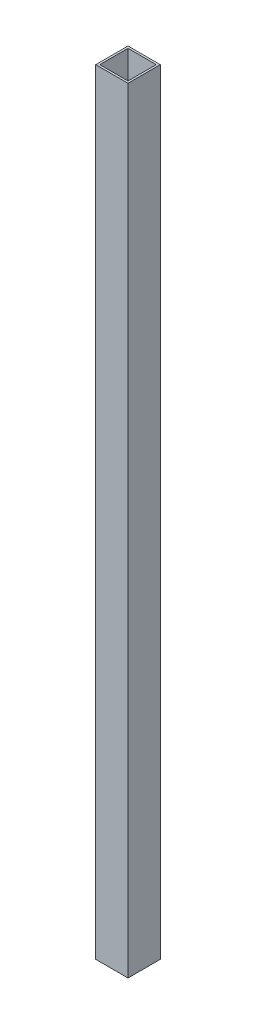
SolidWorks part; units mm, degrees
ref_plane "Front Plane" through (0, 0, 0) normal (0, 0, 1) x (1, 0, 0)
ref_plane "Top Plane" through (0, 0, 0) normal (0, 1, 0) x (1, 0, 0)
ref_plane "Right Plane" through (0, 0, 0) normal (1, 0, 0) x (0, 0, -1)
sketch "Sketch1" plane through (0, 0, 0) normal (0, 1, 0) x (1, 0, 0)
  line L1 (12.7, 12.7) -> (-12.7, 12.7)
  line L2 (12.7, 12.7) -> (12.7, -12.7)
  line L3 (12.7, -12.7) -> (-12.7, -12.7)
  line L4 (-12.7, 12.7) -> (-12.7, -12.7)
  line L5 (12.7, 12.7) -> (-12.7, -12.7) construction
  line L6 (12.7, -12.7) -> (-12.7, 12.7) construction
  line L7 (11.1125, 11.1125) -> (-11.1125, 11.1125)
  line L8 (11.1125, 11.1125) -> (11.1125, -11.1125)
  line L9 (11.1125, -11.1125) -> (-11.1125, -11.1125)
  line L10 (-11.1125, 11.1125) -> (-11.1125, -11.1125)
  line L11 (11.1125, 11.1125) -> (-11.1125, -11.1125) construction
  line L12 (11.1125, -11.1125) -> (-11.1125, 11.1125) construction
  point P0 (0, 0)
  point P6 (0, 0)
  dimension "D1" = 25.4
  dimension "D2" = 25.4
  dimension "D3" = 1.5875
  dimension "D4" = 1.5875
extrude "Boss-Extrude1" add sketch "Sketch1" along normal blind 609.6
